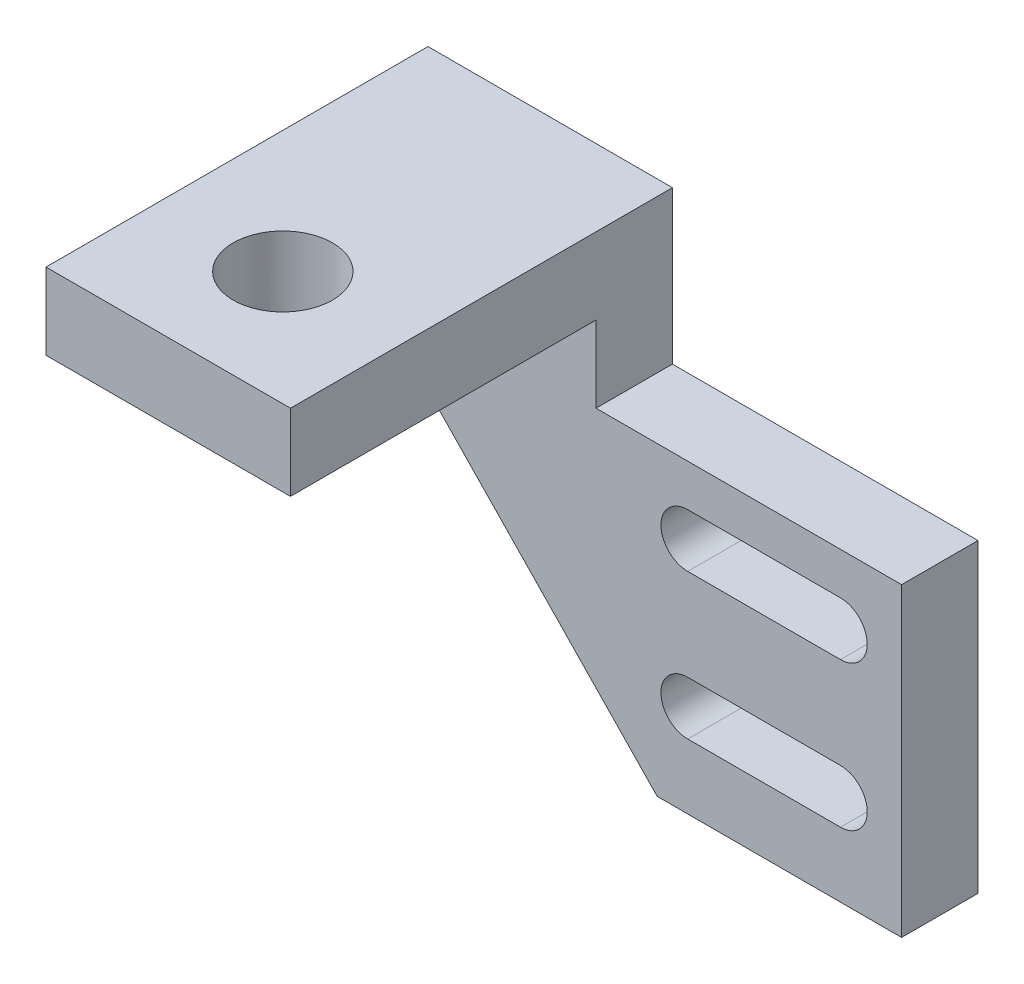
SolidWorks part; units mm, degrees
ref_plane "Piano frontale" through (0, 0, 0) normal (0, 0, 1) x (1, 0, 0)
ref_plane "Piano superiore" through (0, 0, 0) normal (0, 1, 0) x (1, 0, 0)
ref_plane "Piano destro" through (0, 0, 0) normal (1, 0, 0) x (0, 0, -1)
sketch "Schizzo1" plane through (0, 0, 0) normal (0, 0, 1) x (1, 0, 0)
  line L0 (-16, 0) -> (0, 0)
  line L1 (0, 0) -> (0, -10)
  line L3 (0, -10) -> (20, -10)
  line L4 (20, -10) -> (20, -30)
  line L5 (20, -30) -> (4, -30)
  line L6 (4, -30) -> (-16, -9.2952)
  line L7 (-16, -9.2952) -> (-16, 0)
  line L8 (16, -22.25) -> (6, -22.25)
  line L9 (16, -25.75) -> (6, -25.75)
  line L10 (16, -12.75) -> (6, -12.75)
  line L11 (16, -16.25) -> (6, -16.25)
  arc A0 (16, -25.75) -> (16, -22.25) centre (16, -24) ccw
  arc A1 (6, -22.25) -> (6, -25.75) centre (6, -24) ccw
  arc A2 (16, -16.25) -> (16, -12.75) centre (16, -14.5) ccw
  arc A3 (6, -12.75) -> (6, -16.25) centre (6, -14.5) ccw
  dimension "D2" = 20
  dimension "D6" = 1.75
  dimension "D10" = 4
  dimension "D1" = 16
  dimension "D3" = 20
  dimension "D4" = 30
  dimension "D5" = 16
  dimension "D7" = 10
  dimension "D8" = 4.25
  dimension "D9" = 6
  dimension "D11" = 4
  dimension "D12" = 20.7048
extrude "Estrusione-Estrusione1" add sketch "Schizzo1" along normal blind 5
sketch "Schizzo2" plane through (0, 0, 5) normal (0, 0, 1) x (1, 0, 0)
  line L0 (-16, 0) -> (-16, -5)
  line L1 (-16, 0) -> (-16, -9.2952) construction
  line L2 (-16, -5) -> (0, -5)
  line L3 (0, -10) -> (0, 0) construction
  line L4 (0, -5) -> (0, 0)
  line L5 (0, 0) -> (-16, 0)
  dimension "D1" = 5
extrude "Estrusione-Estrusione2" add sketch "Schizzo2" along normal blind 20
sketch "Schizzo3" plane through (0, -5, 0) normal (0, -1, 0) x (1, 0, 0)
  line L2 (-8, 25) -> (-8, 4.0351) construction
  line L3 (-16, 25) -> (0, 25) construction
  circle A0 centre (-8, 17.5) radius 3.25
  dimension "D1" = 6.5
  dimension "D2" = 7.5
extrude "Taglio-Estrusione1" cut sketch "Schizzo3" against normal up to next
